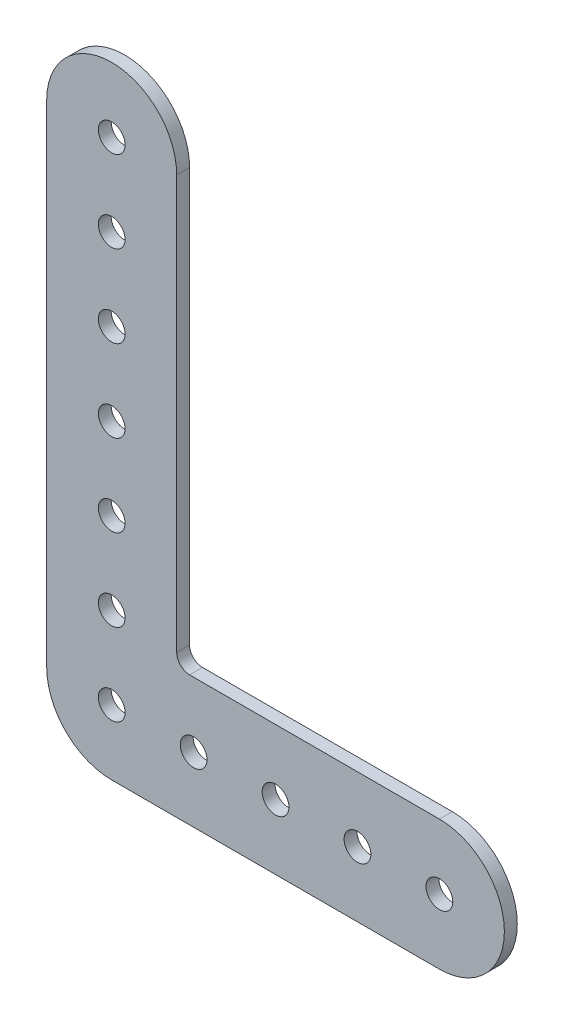
SolidWorks part; units mm, degrees
ref_plane "Front Plane" through (0, 0, 0) normal (0, 0, 1) x (1, 0, 0)
ref_plane "Top Plane" through (0, 0, 0) normal (0, 1, 0) x (1, 0, 0)
ref_plane "Right Plane" through (0, 0, 0) normal (1, 0, 0) x (0, 0, -1)
sketch "Sketch1" plane through (0, 0, 0) normal (0, 0, 1) x (1, 0, 0)
  line L0 (0, 0) -> (0, 66.125) construction
  line L1 (-10.075, 76.2) -> (-10.075, 0)
  line L2 (50.8, 0) -> (48.725, 0) construction
  line L3 (0, -10.075) -> (50.8, -10.075)
  line L4 (10.075, 76.2) -> (10.075, 10.075)
  line L5 (50.8, 10.075) -> (10.075, 10.075)
  line L6 (10.075, 10.075) -> (10.075, 0) construction
  line L7 (48.725, 0) -> (40.725, 0) construction
  line L8 (40.725, 0) -> (0, 0) construction
  line L9 (0, 66.125) -> (0, 74.125) construction
  line L10 (0, 74.125) -> (0, 76.2) construction
  circle A0 centre (0, 0) radius 2.075
  circle A1 centre (12.7, 0) radius 2.075
  circle A2 centre (25.4, 0) radius 2.075
  circle A3 centre (38.1, 0) radius 2.075
  circle A4 centre (50.8, 0) radius 2.075
  circle A5 centre (0, 12.7) radius 2.075
  circle A6 centre (0, 25.4) radius 2.075
  circle A7 centre (0, 38.1) radius 2.075
  circle A8 centre (0, 50.8) radius 2.075
  circle A9 centre (0, 63.5) radius 2.075
  circle A10 centre (0, 76.2) radius 2.075
  arc A11 (10.075, 76.2) -> (-10.075, 76.2) centre (0, 76.2) ccw
  arc A12 (50.8, -10.075) -> (50.8, 10.075) centre (50.8, 0) ccw
  arc A13 (-10.075, 0) -> (0, -10.075) centre (0, 0) ccw
  arc A14 (10.075, 0) -> (0, 10.075) centre (0, 0) ccw construction
  circle A15 centre (0, 0) radius 10.075 construction
  arc A16 (0, 10.075) -> (-10.075, 0) centre (0, 0) ccw construction
  arc A17 (0, -10.075) -> (10.075, 0) centre (0, 0) ccw construction
  arc A18 (40.725, 0) -> (50.8, -10.075) centre (50.8, 0) ccw construction
  circle A19 centre (50.8, 0) radius 10.075 construction
  arc A20 (50.8, 10.075) -> (40.725, 0) centre (50.8, 0) ccw construction
  arc A21 (-10.075, 76.2) -> (0, 66.125) centre (0, 76.2) ccw construction
  circle A22 centre (0, 76.2) radius 10.075 construction
  arc A23 (0, 66.125) -> (10.075, 76.2) centre (0, 76.2) ccw construction
  dimension "D3" = 4.15
  dimension "D1" = 76.2
  dimension "D2" = 50.8
  dimension "D5" = 12.7
  dimension "D7" = 12.7
  dimension "D8" = 8
  dimension "D4" = 5
  dimension "D6" = 7
extrude "Boss-Extrude1" add sketch "Sketch1" along normal mid plane 2
fillet "Fillet1" radius 2 1 edges at (10.075, 10.075, 0)
